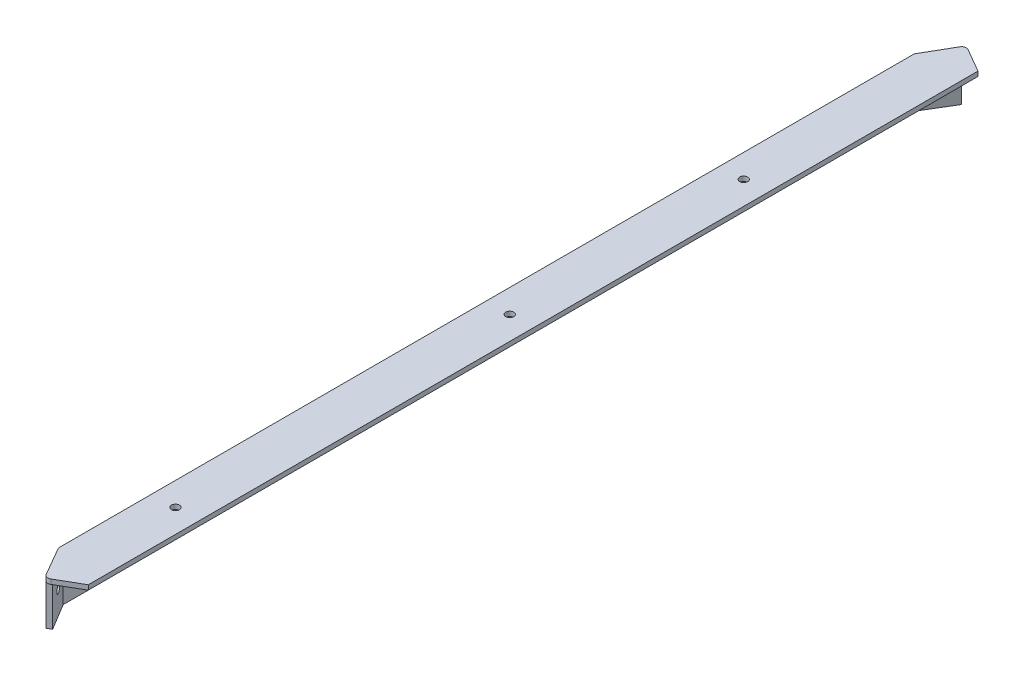
SolidWorks part; units mm, degrees
material "1.0116 (S235J2G3)"
ref_plane "Front Plane" through (0, 0, 0) normal (0, 0, 1) x (1, 0, 0)
ref_plane "Top Plane" through (0, 0, 0) normal (0, 1, 0) x (1, 0, 0)
ref_plane "Right Plane" through (0, 0, 0) normal (1, 0, 0) x (0, 0, -1)
sketch "Sketch1" plane through (0, 0, 0) normal (0, 0, 1) x (1, 0, 0)
  line L6 (0, 0) -> (0, 70)
  line L7 (0, 70) -> (70, 70)
  line L8 (70, 70) -> (70, 63)
  line L9 (70, 63) -> (7, 63)
  line L10 (7, 63) -> (7, 0)
  line L11 (7, 0) -> (0, 0)
  dimension "D1" = 70
  dimension "D2" = 70
  dimension "D3" = 7
  dimension "D4" = 7
extrude "Boss-Extrude1" add sketch "Sketch1" along normal blind 640
sketch "Sketch2" plane through (0, 0, 0) normal (0, 1, 0) x (1, 0, 0)
  line L0 (0, -640) -> (25, -683.3013)
  line L1 (25, -683.3013) -> (31.0622, -679.8013)
  line L2 (31.0622, -679.8013) -> (7, -640)
  line L3 (0, -640) -> (7, -640) construction
  line L4 (7, -640) -> (0, -640)
  line L5 (0, -640) -> (0, 0) construction
  dimension "D1" = 46.5095
  dimension "D2" = 50
  dimension "D3" = 210
  dimension "D4" = 7
extrude "Boss-Extrude2" add sketch "Sketch2" along normal blind 63
sketch "Sketch9" plane through (0, 63, 0) normal (0, 1, 0) x (1, 0, 0)
  line L0 (0, -640) -> (25, -683.3013)
  line L1 (34.5622, -685.8634) -> (70, -665.4034)
  line L2 (70, -665.4034) -> (70, -640)
  line L3 (70, -640) -> (0, -640)
  arc A0 (25, -683.3013) -> (34.5622, -685.8634) centre (31.0622, -679.8013) ccw
  dimension "D5" = 14
  dimension "D2" = 40.9201
  dimension "D1" = 90
  dimension "D3" = 90
  dimension "D4" = 60
  dimension "D6" = 7
  dimension "D7" = 7
extrude "Boss-Extrude4" add sketch "Sketch9" along normal blind 7
sketch "Sketch10" plane through (-278.2276, 0, 168.2047) normal (0.8558, 0, -0.5174) x (-0.5174, 0, -0.8558)
  line L0 (-597.822, 63) -> (-597.822, 0) construction
  line L1 (-597.822, 0) -> (-551.3126, 0) construction
  circle A0 centre (-572.822, 35) radius 6
  dimension "D1" = 12
  dimension "D2" = 25
  dimension "D3" = 35
extrude "Cut-Extrude3" cut sketch "Sketch10" against normal blind 7
sketch "Sketch21" plane through (0, 0, 0) normal (0, 0, -1) x (-1, 0, 0)
  line L0 (0, 70) -> (-70, 70) construction
  line L1 (-70, 70) -> (-70, 0) construction
  line L2 (-70, 0) -> (0, 0) construction
  line L3 (0, 0) -> (0, 69.2595) construction
fillet "Fillet5" radius 5 2 edges at (19.0311, 63, 659.9006) (7, 63, 320)
mirror "Mirror6" about plane through (0, 0, 0) normal (0, 0, 1) of bodies 107 108
sketch "Sketch22" plane through (0, 70, 0) normal (0, 1, 0) x (1, 0, 0)
  line L0 (70, 0) -> (0, 0) construction
  line L1 (0, -38.5) -> (0, 38.5) construction
  circle A0 centre (35, 0) radius 6
  circle A1 centre (35, 350) radius 6
  circle A2 centre (35, -500) radius 6
  dimension "D1" = 12
  dimension "D2" = 12
  dimension "D3" = 12
  dimension "D4" = 350
  dimension "D5" = 500
  dimension "D6" = 35
  dimension "D7" = 35
extrude "Cut-Extrude4" cut sketch "Sketch22" against normal blind 335
